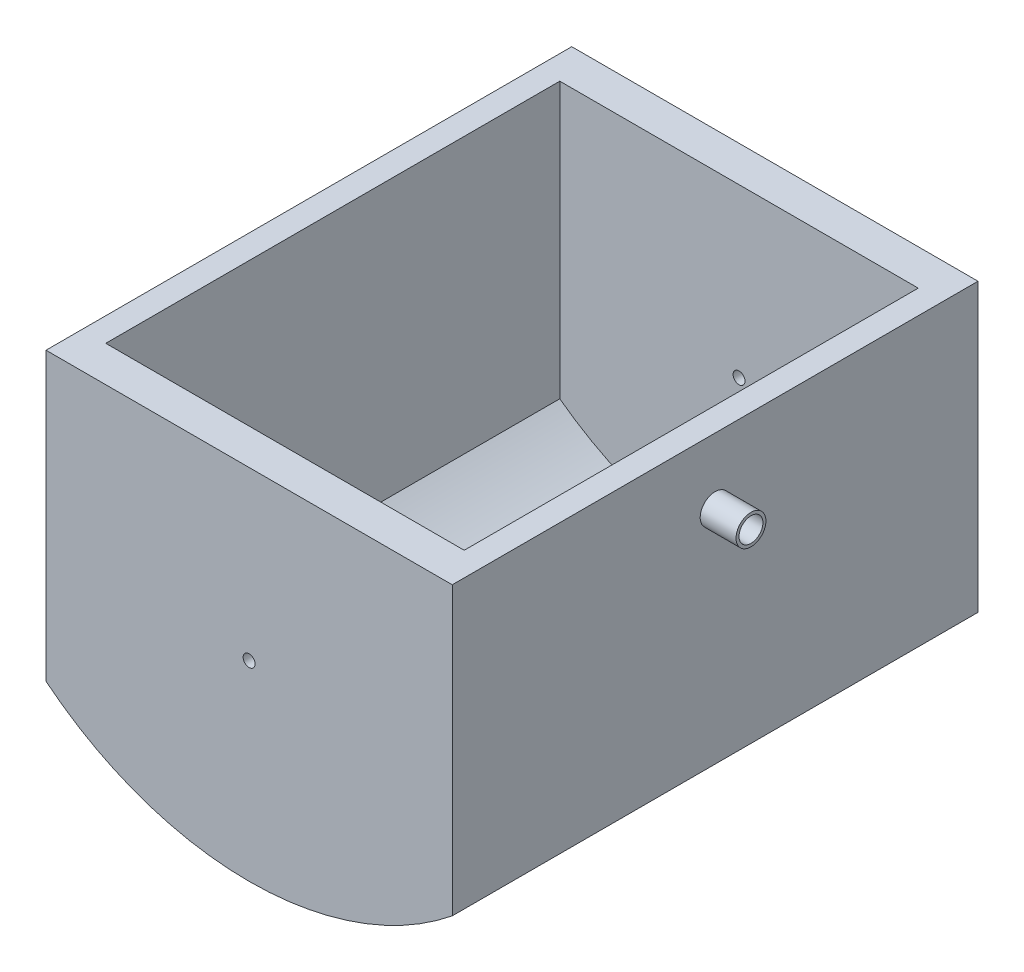
SolidWorks part; units mm, degrees
ref_plane "Front Plane" through (0, 0, 0) normal (0, 0, 1) x (1, 0, 0)
ref_plane "Top Plane" through (0, 0, 0) normal (0, 1, 0) x (1, 0, 0)
ref_plane "Right Plane" through (0, 0, 0) normal (1, 0, 0) x (0, 0, -1)
sketch "Sketch1" plane through (0, 0, 0) normal (0, 0, 1) x (1, 0, 0)
  line L0 (-170, 140) -> (170, 140)
  line L1 (-170, 140) -> (-170, -100)
  line L2 (170, 140) -> (170, -100)
  line L3 (-170, -100) -> (170, -100) construction
  line L4 (-170, -100) -> (-170, -160) construction
  line L5 (-170, -160) -> (149.7845, -160) construction
  circle A0 centre (0, 0) radius 5
  arc A1 (-170, -100) -> (170, -100) centre (0, 110.8333) ccw
  point P4 (0, 140)
  dimension "D1" = 10
  dimension "D2" = 340
  dimension "D3" = 240
  dimension "D4" = 240
  dimension "D5" = 140
  dimension "D6" = 60
extrude "Boss-Extrude1" add sketch "Sketch1" along normal mid plane 440
sketch "Sketch3" plane through (0, 0, 0) normal (0, 0, 1) x (1, 0, 0)
  line L0 (-170, 140) -> (-170, -100) construction
  line L1 (-150, 140) -> (150, 140)
  line L2 (170, -100) -> (170, 140) construction
  line L3 (170, 140) -> (-170, 140) construction
  line L4 (-80, -126.9005) -> (-80, -159.8899)
  line L5 (80, -126.9005) -> (80, -159.8899)
  line L6 (150, 140) -> (150, -90.2074)
  line L7 (-150, 140) -> (-150, -90.2074)
  arc A1 (-150, -90.2074) -> (-80, -126.9005) centre (0, 110.8333) ccw
  arc A2 (-170, -100) -> (170, -100) centre (0, 110.8333) ccw construction
  arc A3 (-80, -159.8899) -> (80, -159.8899) centre (0, 110.8333) ccw
  arc A4 (80, -126.9005) -> (150, -90.2074) centre (0, 110.8333) ccw
  dimension "D1" = 20
  dimension "D2" = 160
  dimension "D3" = 20
  dimension "D4" = 20
extrude "Cut-Extrude1" cut sketch "Sketch3" against normal mid plane 380
sketch "Sketch4" plane through (150, 0, 0) normal (-1, 0, 0) x (0, 0, 1)
  line L1 (220, 140) -> (-220, 140) construction
  line L2 (220, 140) -> (220, -100) construction
  circle A0 centre (0, 85) radius 10
  dimension "D1" = 20
  dimension "D2" = 55
  dimension "D3" = 220
extrude "Cut-Extrude2" cut sketch "Sketch4" against normal mid plane 380
sketch "Sketch5" plane through (170, 0, 0) normal (1, 0, 0) x (0, 0, -1)
  circle A0 centre (0, 85) radius 10
  circle A1 centre (0, 85) radius 12.5
  dimension "D1" = 20
  dimension "D2" = 25
extrude "Boss-Extrude2" add sketch "Sketch5" along normal blind 30
